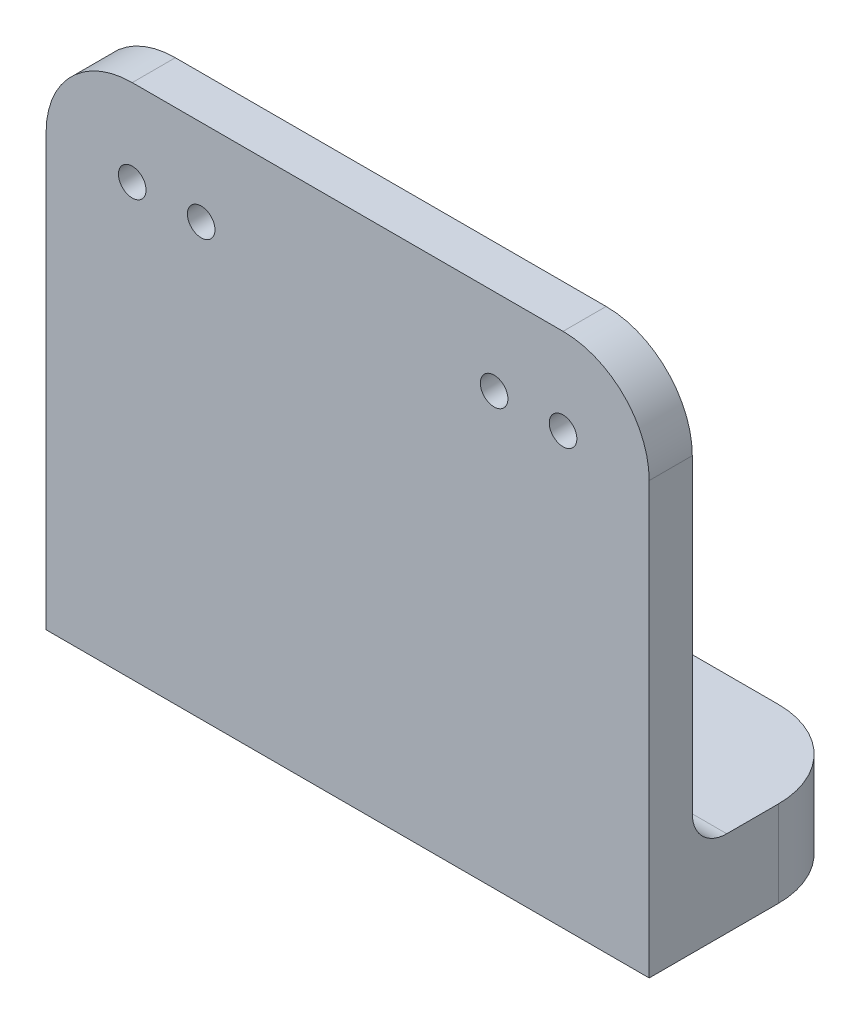
SolidWorks part; units mm, degrees
ref_plane "Front Plane" through (0, 0, 0) normal (0, 0, 1) x (1, 0, 0)
ref_plane "Top Plane" through (0, 0, 0) normal (0, 1, 0) x (1, 0, 0)
ref_plane "Right Plane" through (0, 0, 0) normal (1, 0, 0) x (0, 0, -1)
sketch "Sketch1" plane through (0, 0, 0) normal (0, 1, 0) x (1, 0, 0)
  line L0 (0, 15) -> (70, 15) construction
  line L1 (0, 0) -> (70, 0)
  line L2 (0, 0) -> (0, 25)
  line L3 (0, 25) -> (70, 25)
  line L4 (70, 0) -> (70, 25)
  circle A0 centre (20, 15) radius 1.6
  circle A1 centre (50, 15) radius 1.6
  dimension "D3" = 20
  dimension "D4" = 20
  dimension "D6" = 3.2
  dimension "D1" = 25
  dimension "D2" = 70
  dimension "D5" = 15
extrude "Boss-Extrude2" add sketch "Sketch1" along normal blind 10
sketch "Sketch2" plane through (0, 10, 0) normal (0, 1, 0) x (1, 0, 0)
  line L0 (0, 25) -> (0, 0) construction
  line L1 (0, 0) -> (70, 0)
  line L2 (0, 0) -> (0, 5)
  line L3 (0, 5) -> (70, 5)
  line L4 (70, 0) -> (70, 5)
  line L5 (70, 0) -> (70, 25) construction
  line L7 (0, 0) -> (70, 0) construction
  dimension "D1" = 5
extrude "Boss-Extrude3" add sketch "Sketch2" along normal blind 50
sketch "Sketch3" plane through (0, 10, 0) normal (0, 1, 0) x (1, 0, 0)
  circle A0 centre (20, 15) radius 3.5
  circle A1 centre (50, 15) radius 3.5
  dimension "D1" = 7
extrude "Cut-Extrude1" cut sketch "Sketch3" against normal blind 5
fillet "Fillet1" radius 4 1 edges at (35, 10, -5)
fillet "Fillet2" radius 10 4 edges at (0, 60, -2.5) (70, 60, -2.5) (70, 5, -25) (0, 5, -25)
sketch "Sketch4" plane through (0, 0, 0) normal (0, 0, 1) x (1, 0, 0)
  line L0 (35, 60) -> (35, 0) construction
  line L1 (10, 60) -> (60, 60) construction
  line L2 (0, 0) -> (70, 0) construction
  line L3 (0, 50) -> (70, 50) construction
  line L4 (0, 50) -> (0, 0) construction
  line L5 (70, 50) -> (70, 0) construction
  circle A0 centre (10, 50) radius 1.6
  circle A1 centre (18, 50) radius 1.6
  circle A2 centre (52, 50) radius 1.6
  circle A3 centre (60, 50) radius 1.6
  dimension "D1" = 3.2
  dimension "D3" = 8
  dimension "D2" = 10
  dimension "D4" = 10
extrude "Cut-Extrude2" cut sketch "Sketch4" against normal through all
